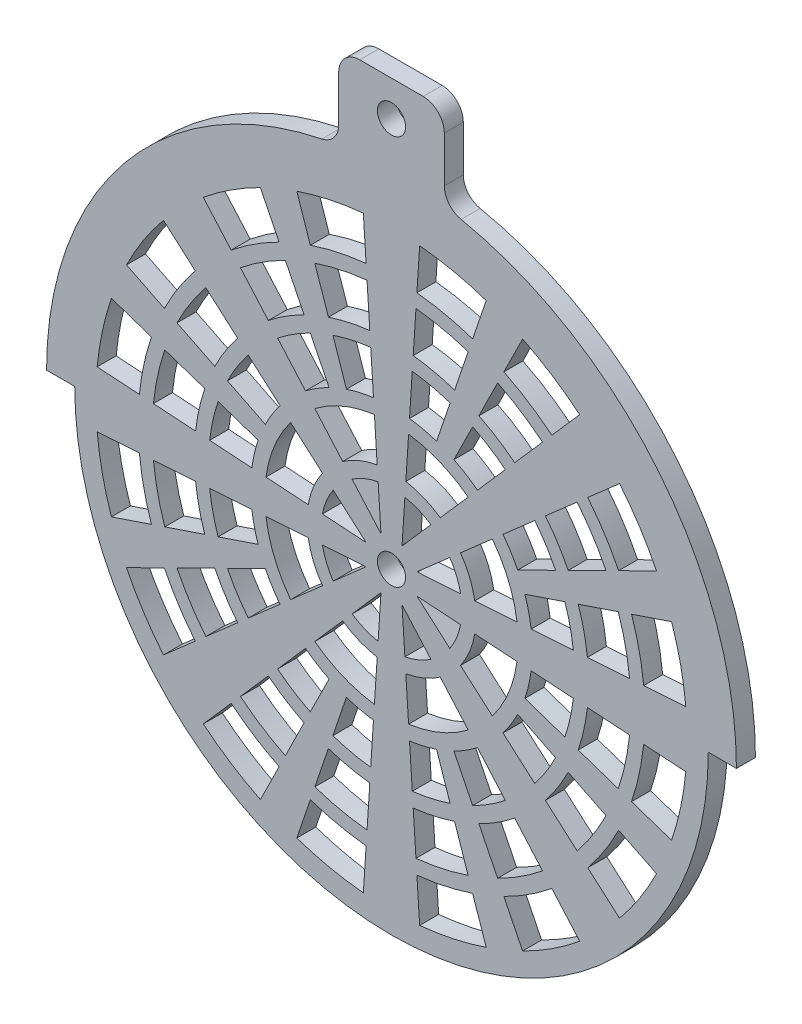
SolidWorks part; units mm, degrees
ref_plane "前基準面" through (0, 0, 0) normal (0, 0, 1) x (1, 0, 0)
ref_plane "上基準面" through (0, 0, 0) normal (0, 1, 0) x (1, 0, 0)
ref_plane "右基準面" through (0, 0, 0) normal (1, 0, 0) x (0, 0, -1)
sketch "草圖1" plane through (0, 0, 0) normal (0, 0, 1) x (1, 0, 0)
  line L0 (-49, 0) -> (-45, 0)
  line L1 (45, 0) -> (49, 0)
  arc A0 (49, 0) -> (-49, 0) centre (0, 0) ccw
  arc A1 (-45, 0) -> (45, 0) centre (0, 0) ccw
  circle A2 centre (0, 0) radius 42
  dimension "D1" = 98
  dimension "D2" = 90
  dimension "D3" = 3
extrude "填料-伸長1" add sketch "草圖1" along normal blind 2.7
sketch "草圖2" plane through (0, 0, 2.7) normal (0, 0, 1) x (1, 0, 0)
  line L0 (0, 4) -> (0, 42) construction
  line L1 (-1.5, 3.7081) -> (-1.9009, 9.8177)
  line L2 (1.5, 3.7081) -> (1.9009, 9.8177)
  line L3 (3.6827, 1.5614) -> (8.2863, 5.598)
  line L4 (1.5614, 3.6827) -> (5.598, 8.2863)
  line L5 (3.7081, -1.5) -> (9.8177, -1.9009)
  line L6 (3.7081, 1.5) -> (9.8177, 1.9009)
  line L7 (1.5614, -3.6827) -> (5.598, -8.2863)
  line L8 (3.6827, -1.5614) -> (8.2863, -5.598)
  line L9 (-1.5, -3.7081) -> (-1.9009, -9.8177)
  line L10 (1.5, -3.7081) -> (1.9009, -9.8177)
  line L11 (-3.6827, -1.5614) -> (-8.2863, -5.598)
  line L12 (-1.5614, -3.6827) -> (-5.598, -8.2863)
  line L13 (-3.7081, 1.5) -> (-9.8177, 1.9009)
  line L14 (-3.7081, -1.5) -> (-9.8177, -1.9009)
  line L15 (-1.5614, 3.6827) -> (-5.598, 8.2863)
  line L16 (-3.6827, 1.5614) -> (-8.2863, 5.598)
  line L17 (1.5307, 3.6955) -> (16.0727, 38.8029) construction
  line L22 (18.947, 6.4041) -> (24.6311, 8.3253)
  line L23 (17.9266, 8.8678) -> (23.3045, 11.5282)
  line L24 (8.8691, 17.9259) -> (15.0775, 30.474)
  line L25 (6.4055, 18.9465) -> (8.3272, 24.6304)
  line L26 (17.9259, -8.8691) -> (23.3037, -11.5299)
  line L27 (18.9465, -6.4055) -> (24.6304, -8.3272)
  line L28 (6.4041, -18.947) -> (8.3253, -24.6311)
  line L29 (8.8678, -17.9266) -> (11.5282, -23.3045)
  line L30 (-8.8691, -17.9259) -> (-11.5299, -23.3037)
  line L31 (-6.4055, -18.9465) -> (-8.3272, -24.6304)
  line L32 (-18.947, -6.4041) -> (-24.6311, -8.3253)
  line L33 (-17.9266, -8.8678) -> (-23.3045, -11.5282)
  line L34 (-17.9259, 8.8691) -> (-23.3037, 11.5299)
  line L35 (-18.9465, 6.4055) -> (-24.6304, 8.3272)
  line L36 (-6.4041, 18.947) -> (-8.3253, 24.6311)
  line L37 (-8.8678, 17.9266) -> (-11.5282, 23.3045)
  line L38 (-3.6069, 35.8188) -> (-4, 41.8091)
  line L39 (3.6069, 35.8188) -> (4, 41.8091)
  line L40 (11.5299, 34.1037) -> (13.4516, 39.7876)
  line L41 (15.9645, 32.2666) -> (18.6252, 37.6444)
  line L42 (22.7773, 27.8782) -> (26.7351, 32.3919)
  line L43 (27.8782, 22.7773) -> (32.3919, 26.7351)
  line L44 (32.2678, 15.9621) -> (37.6458, 18.6224)
  line L45 (34.1045, 11.5274) -> (39.7886, 13.4486)
  line L46 (-11.5274, 34.1045) -> (-13.4486, 39.7886)
  line L47 (-15.9621, 32.2678) -> (-18.6224, 37.6458)
  line L48 (-22.7773, 27.8782) -> (-26.7351, 32.3919)
  line L49 (-27.8782, 22.7773) -> (-32.3919, 26.7351)
  line L50 (-32.2666, 15.9645) -> (-37.6444, 18.6252)
  line L51 (-34.1037, 11.5299) -> (-39.7876, 13.4516)
  line L52 (-35.8188, 3.6069) -> (-41.8091, 4)
  line L53 (-35.8188, -3.6069) -> (-41.8091, -4)
  line L54 (-34.1045, -11.5274) -> (-39.7886, -13.4486)
  line L55 (-32.2678, -15.9621) -> (-37.6458, -18.6224)
  line L56 (-27.8782, -22.7773) -> (-32.3919, -26.7351)
  line L57 (-22.7773, -27.8782) -> (-26.7351, -32.3919)
  line L58 (-15.9645, -32.2666) -> (-18.6252, -37.6444)
  line L59 (-11.5299, -34.1037) -> (-13.4516, -39.7876)
  line L60 (-3.6069, -35.8188) -> (-4, -41.8091)
  line L61 (3.6069, -35.8188) -> (4, -41.8091)
  line L62 (11.5274, -34.1045) -> (13.4486, -39.7886)
  line L63 (15.9621, -32.2678) -> (18.6224, -37.6458)
  line L64 (22.7773, -27.8782) -> (26.7351, -32.3919)
  line L65 (27.8782, -22.7773) -> (32.3919, -26.7351)
  line L66 (32.2666, -15.9645) -> (37.6444, -18.6252)
  line L67 (35.8188, -3.6069) -> (41.8091, -4)
  line L68 (34.1037, -11.5299) -> (39.7876, -13.4516)
  line L69 (35.8188, 3.6069) -> (41.8091, 4)
  line L70 (17.4988, 21.8585) -> (21.4578, 26.3735)
  line L71 (21.8585, 17.4988) -> (26.3735, 21.4578)
  line L72 (25.0972, 12.4149) -> (30.4752, 15.0753)
  line L73 (26.5258, 8.9657) -> (32.2098, 10.887)
  line L74 (27.8298, 3.0827) -> (33.8219, 3.4759)
  line L75 (27.8298, -3.0827) -> (33.8219, -3.4759)
  line L76 (26.5251, -8.9677) -> (32.209, -10.8894)
  line L77 (25.0963, -12.4168) -> (30.474, -15.0775)
  line L78 (21.8585, -17.4988) -> (26.3735, -21.4578)
  line L79 (17.4988, -21.8585) -> (21.4578, -26.3735)
  line L80 (12.4149, -25.0972) -> (15.0753, -30.4752)
  line L81 (8.9657, -26.5258) -> (10.887, -32.2098)
  line L82 (3.0827, -27.8298) -> (3.4759, -33.8219)
  line L83 (-3.0827, -27.8298) -> (-3.4759, -33.8219)
  line L84 (-8.9677, -26.5251) -> (-10.8894, -32.209)
  line L85 (-12.4168, -25.0963) -> (-15.0775, -30.474)
  line L86 (-17.4988, -21.8585) -> (-21.4578, -26.3735)
  line L87 (-21.8585, -17.4988) -> (-26.3735, -21.4578)
  line L88 (-25.0972, -12.4149) -> (-30.4752, -15.0753)
  line L89 (-26.5258, -8.9657) -> (-32.2098, -10.887)
  line L90 (-27.8298, -3.0827) -> (-33.8219, -3.4759)
  line L91 (-27.8298, 3.0827) -> (-33.8219, 3.4759)
  line L92 (-26.5251, 8.9677) -> (-32.209, 10.8894)
  line L93 (-25.0963, 12.4168) -> (-30.474, 15.0775)
  line L94 (-21.8585, 17.4988) -> (-26.3735, 21.4578)
  line L95 (-17.4988, 21.8585) -> (-21.4578, 26.3735)
  line L96 (-12.4149, 25.0972) -> (-15.0753, 30.4752)
  line L97 (-8.9657, 26.5258) -> (-10.887, 32.2098)
  line L98 (-3.0827, 27.8298) -> (-3.4759, 33.8219)
  line L99 (3.0827, 27.8298) -> (3.4759, 33.8219)
  line L100 (8.9677, 26.5251) -> (10.8894, 32.209)
  line L101 (-12.217, 15.8349) -> (-16.1788, 20.3531)
  line L102 (-15.8349, 12.217) -> (-20.3531, 16.1788)
  line L103 (-19.8357, 2.5582) -> (-25.8319, 2.9517)
  line L104 (-19.8357, -2.5582) -> (-25.8319, -2.9517)
  line L105 (-15.8349, -12.217) -> (-20.3531, -16.1788)
  line L106 (-12.217, -15.8349) -> (-16.1788, -20.3531)
  line L107 (-2.5582, -19.8357) -> (-2.9517, -25.8319)
  line L108 (2.5582, -19.8357) -> (2.9517, -25.8319)
  line L109 (12.217, -15.8349) -> (16.1788, -20.3531)
  line L110 (15.8349, -12.217) -> (20.3531, -16.1788)
  line L111 (19.8357, -2.5582) -> (25.8319, -2.9517)
  line L112 (19.8357, 2.5582) -> (25.8319, 2.9517)
  line L113 (15.8349, 12.217) -> (20.3531, 16.1788)
  line L114 (12.217, 15.8349) -> (16.1788, 20.3531)
  line L115 (-2.5582, 19.8357) -> (-2.9517, 25.8319)
  line L116 (2.5582, 19.8357) -> (2.9517, 25.8319)
  line L117 (6.9253, -9.8) -> (10.8956, -14.3278)
  line L118 (9.8, -6.9253) -> (14.3278, -10.8956)
  line L119 (11.8266, -2.0327) -> (17.8356, -2.427)
  line L120 (11.8266, 2.0327) -> (17.8356, 2.427)
  line L121 (9.8, 6.9253) -> (14.3278, 10.8956)
  line L122 (6.9253, 9.8) -> (10.8956, 14.3278)
  line L123 (2.0327, 11.8266) -> (2.427, 17.8356)
  line L124 (-2.0327, 11.8266) -> (-2.427, 17.8356)
  line L125 (-6.9253, 9.8) -> (-10.8956, 14.3278)
  line L126 (-9.8, 6.9253) -> (-14.3278, 10.8956)
  line L127 (-11.8266, 2.0327) -> (-17.8356, 2.427)
  line L128 (-11.8266, -2.0327) -> (-17.8356, -2.427)
  line L129 (-9.8, -6.9253) -> (-14.3278, -10.8956)
  line L130 (-6.9253, -9.8) -> (-10.8956, -14.3278)
  line L131 (-2.0327, -11.8266) -> (-2.427, -17.8356)
  line L132 (2.0327, -11.8266) -> (2.427, -17.8356)
  arc A0 (8.9677, 26.5251) -> (3.0827, 27.8298) centre (0, 0) ccw
  arc A1 (21.4578, 26.3735) -> (15.0775, 30.474) centre (0, 0) ccw
  circle A2 centre (0, 0) radius 36
  arc A3 (22.7773, 27.8782) -> (15.9645, 32.2666) centre (0, 0) ccw
  arc A6 (22.7773, 27.8782) -> (15.9645, 32.2666) centre (0, 0) ccw
  arc A7 (21.4578, 26.3735) -> (15.0775, 30.474) centre (0, 0) ccw
  arc A8 (-11.5282, 23.3045) -> (-16.1788, 20.3531) centre (0, 0) ccw
  arc A9 (-8.8678, 17.9266) -> (-12.217, 15.8349) centre (0, 0) ccw
  arc A10 (-2.427, 17.8356) -> (-10.8956, 14.3278) centre (0, 0) ccw
  arc A11 (-6.9253, -9.8) -> (-2.0327, -11.8266) centre (0, 0) ccw
  arc A12 (-5.598, -8.2863) -> (-1.9009, -9.8177) centre (0, 0) ccw
  arc A14 (-3.6827, 1.5614) -> (-3.7081, 1.5) centre (0, 0) ccw
  circle A15 centre (0, 0) radius 42 construction
  arc A16 (4, 41.8091) -> (-4, 41.8091) centre (0, 0) ccw
  arc A17 (18.6252, 37.6444) -> (13.4516, 39.7876) centre (0, 0) ccw
  arc A18 (32.3919, 26.7351) -> (26.7351, 32.3919) centre (0, 0) ccw
  arc A19 (39.7886, 13.4486) -> (37.6458, 18.6224) centre (0, 0) ccw
  arc A20 (41.8091, -4) -> (41.8091, 4) centre (0, 0) ccw
  arc A21 (37.6444, -18.6252) -> (39.7876, -13.4516) centre (0, 0) ccw
  arc A22 (26.7351, -32.3919) -> (32.3919, -26.7351) centre (0, 0) ccw
  arc A23 (13.4486, -39.7886) -> (18.6224, -37.6458) centre (0, 0) ccw
  arc A24 (-4, -41.8091) -> (4, -41.8091) centre (0, 0) ccw
  arc A25 (-18.6252, -37.6444) -> (-13.4516, -39.7876) centre (0, 0) ccw
  arc A26 (-32.3919, -26.7351) -> (-26.7351, -32.3919) centre (0, 0) ccw
  arc A27 (-39.7886, -13.4486) -> (-37.6458, -18.6224) centre (0, 0) ccw
  arc A28 (-41.8091, 4) -> (-41.8091, -4) centre (0, 0) ccw
  arc A29 (-37.6444, 18.6252) -> (-39.7876, 13.4516) centre (0, 0) ccw
  arc A30 (-26.7351, 32.3919) -> (-32.3919, 26.7351) centre (0, 0) ccw
  arc A31 (-13.4486, 39.7886) -> (-18.6224, 37.6458) centre (0, 0) ccw
  circle A32 centre (0, 0) radius 36 construction
  circle A33 centre (0, 0) radius 34 construction
  arc A34 (32.2678, 15.9621) -> (27.8782, 22.7773) centre (0, 0) ccw
  arc A35 (32.2678, 15.9621) -> (27.8782, 22.7773) centre (0, 0) ccw
  arc A36 (30.4752, 15.0753) -> (26.3735, 21.4578) centre (0, 0) ccw
  arc A37 (30.4752, 15.0753) -> (26.3735, 21.4578) centre (0, 0) ccw
  arc A38 (35.8188, 3.6069) -> (34.1045, 11.5274) centre (0, 0) ccw
  arc A39 (35.8188, 3.6069) -> (34.1045, 11.5274) centre (0, 0) ccw
  arc A40 (33.8219, 3.4759) -> (32.2098, 10.887) centre (0, 0) ccw
  arc A41 (33.8219, 3.4759) -> (32.2098, 10.887) centre (0, 0) ccw
  arc A42 (34.1037, -11.5299) -> (35.8188, -3.6069) centre (0, 0) ccw
  arc A43 (34.1037, -11.5299) -> (35.8188, -3.6069) centre (0, 0) ccw
  arc A44 (32.209, -10.8894) -> (33.8219, -3.4759) centre (0, 0) ccw
  arc A45 (32.209, -10.8894) -> (33.8219, -3.4759) centre (0, 0) ccw
  arc A46 (27.8782, -22.7773) -> (32.2666, -15.9645) centre (0, 0) ccw
  arc A47 (27.8782, -22.7773) -> (32.2666, -15.9645) centre (0, 0) ccw
  arc A48 (26.3735, -21.4578) -> (30.474, -15.0775) centre (0, 0) ccw
  arc A49 (26.3735, -21.4578) -> (30.474, -15.0775) centre (0, 0) ccw
  arc A50 (15.9621, -32.2678) -> (22.7773, -27.8782) centre (0, 0) ccw
  arc A51 (15.9621, -32.2678) -> (22.7773, -27.8782) centre (0, 0) ccw
  arc A52 (15.0753, -30.4752) -> (21.4578, -26.3735) centre (0, 0) ccw
  arc A53 (15.0753, -30.4752) -> (21.4578, -26.3735) centre (0, 0) ccw
  arc A54 (3.6069, -35.8188) -> (11.5274, -34.1045) centre (0, 0) ccw
  arc A55 (3.6069, -35.8188) -> (11.5274, -34.1045) centre (0, 0) ccw
  arc A56 (3.4759, -33.8219) -> (10.887, -32.2098) centre (0, 0) ccw
  arc A57 (3.4759, -33.8219) -> (10.887, -32.2098) centre (0, 0) ccw
  arc A58 (-11.5299, -34.1037) -> (-3.6069, -35.8188) centre (0, 0) ccw
  arc A59 (-11.5299, -34.1037) -> (-3.6069, -35.8188) centre (0, 0) ccw
  arc A60 (-10.8894, -32.209) -> (-3.4759, -33.8219) centre (0, 0) ccw
  arc A61 (-10.8894, -32.209) -> (-3.4759, -33.8219) centre (0, 0) ccw
  arc A62 (-22.7773, -27.8782) -> (-15.9645, -32.2666) centre (0, 0) ccw
  arc A63 (-22.7773, -27.8782) -> (-15.9645, -32.2666) centre (0, 0) ccw
  arc A64 (-21.4578, -26.3735) -> (-15.0775, -30.474) centre (0, 0) ccw
  arc A65 (-21.4578, -26.3735) -> (-15.0775, -30.474) centre (0, 0) ccw
  arc A66 (-32.2678, -15.9621) -> (-27.8782, -22.7773) centre (0, 0) ccw
  arc A67 (-32.2678, -15.9621) -> (-27.8782, -22.7773) centre (0, 0) ccw
  arc A68 (-30.4752, -15.0753) -> (-26.3735, -21.4578) centre (0, 0) ccw
  arc A69 (-30.4752, -15.0753) -> (-26.3735, -21.4578) centre (0, 0) ccw
  arc A70 (-35.8188, -3.6069) -> (-34.1045, -11.5274) centre (0, 0) ccw
  arc A71 (-35.8188, -3.6069) -> (-34.1045, -11.5274) centre (0, 0) ccw
  arc A72 (-33.8219, -3.4759) -> (-32.2098, -10.887) centre (0, 0) ccw
  arc A73 (-33.8219, -3.4759) -> (-32.2098, -10.887) centre (0, 0) ccw
  arc A74 (-34.1037, 11.5299) -> (-35.8188, 3.6069) centre (0, 0) ccw
  arc A75 (-34.1037, 11.5299) -> (-35.8188, 3.6069) centre (0, 0) ccw
  arc A76 (-32.209, 10.8894) -> (-33.8219, 3.4759) centre (0, 0) ccw
  arc A77 (-32.209, 10.8894) -> (-33.8219, 3.4759) centre (0, 0) ccw
  arc A78 (-27.8782, 22.7773) -> (-32.2666, 15.9645) centre (0, 0) ccw
  arc A79 (-27.8782, 22.7773) -> (-32.2666, 15.9645) centre (0, 0) ccw
  arc A80 (-26.3735, 21.4578) -> (-30.474, 15.0775) centre (0, 0) ccw
  arc A81 (-26.3735, 21.4578) -> (-30.474, 15.0775) centre (0, 0) ccw
  arc A82 (-15.9621, 32.2678) -> (-22.7773, 27.8782) centre (0, 0) ccw
  arc A83 (-15.9621, 32.2678) -> (-22.7773, 27.8782) centre (0, 0) ccw
  arc A84 (-15.0753, 30.4752) -> (-21.4578, 26.3735) centre (0, 0) ccw
  arc A85 (-15.0753, 30.4752) -> (-21.4578, 26.3735) centre (0, 0) ccw
  arc A86 (11.5299, 34.1037) -> (3.6069, 35.8188) centre (0, 0) ccw
  arc A87 (11.5299, 34.1037) -> (3.6069, 35.8188) centre (0, 0) ccw
  arc A88 (10.8894, 32.209) -> (3.4759, 33.8219) centre (0, 0) ccw
  arc A89 (10.8894, 32.209) -> (3.4759, 33.8219) centre (0, 0) ccw
  circle A90 centre (0, 0) radius 28 construction
  arc A91 (-3.0827, 27.8298) -> (-8.9657, 26.5258) centre (0, 0) ccw
  arc A92 (-3.6069, 35.8188) -> (-11.5274, 34.1045) centre (0, 0) ccw
  arc A93 (-3.6069, 35.8188) -> (-11.5274, 34.1045) centre (0, 0) ccw
  arc A94 (-3.4759, 33.8219) -> (-10.887, 32.2098) centre (0, 0) ccw
  arc A95 (-3.4759, 33.8219) -> (-10.887, 32.2098) centre (0, 0) ccw
  arc A96 (-12.4149, 25.0972) -> (-17.4988, 21.8585) centre (0, 0) ccw
  circle A97 centre (0, 0) radius 26 construction
  arc A98 (-21.8585, 17.4988) -> (-25.0963, 12.4168) centre (0, 0) ccw
  arc A99 (-20.3531, 16.1788) -> (-23.3037, 11.5299) centre (0, 0) ccw
  arc A100 (-26.5251, 8.9677) -> (-27.8298, 3.0827) centre (0, 0) ccw
  arc A101 (-24.6304, 8.3272) -> (-25.8319, 2.9517) centre (0, 0) ccw
  arc A102 (-27.8298, -3.0827) -> (-26.5258, -8.9657) centre (0, 0) ccw
  arc A103 (-25.8319, -2.9517) -> (-24.6311, -8.3253) centre (0, 0) ccw
  arc A104 (-25.0972, -12.4149) -> (-21.8585, -17.4988) centre (0, 0) ccw
  arc A105 (-23.3045, -11.5282) -> (-20.3531, -16.1788) centre (0, 0) ccw
  arc A106 (-17.4988, -21.8585) -> (-12.4168, -25.0963) centre (0, 0) ccw
  arc A107 (-16.1788, -20.3531) -> (-11.5299, -23.3037) centre (0, 0) ccw
  arc A108 (-8.9677, -26.5251) -> (-3.0827, -27.8298) centre (0, 0) ccw
  arc A109 (-8.3272, -24.6304) -> (-2.9517, -25.8319) centre (0, 0) ccw
  arc A110 (3.0827, -27.8298) -> (8.9657, -26.5258) centre (0, 0) ccw
  arc A111 (2.9517, -25.8319) -> (8.3253, -24.6311) centre (0, 0) ccw
  arc A112 (12.4149, -25.0972) -> (17.4988, -21.8585) centre (0, 0) ccw
  arc A113 (11.5282, -23.3045) -> (16.1788, -20.3531) centre (0, 0) ccw
  arc A114 (21.8585, -17.4988) -> (25.0963, -12.4168) centre (0, 0) ccw
  arc A115 (20.3531, -16.1788) -> (23.3037, -11.5299) centre (0, 0) ccw
  arc A116 (26.5251, -8.9677) -> (27.8298, -3.0827) centre (0, 0) ccw
  arc A117 (24.6304, -8.3272) -> (25.8319, -2.9517) centre (0, 0) ccw
  arc A118 (27.8298, 3.0827) -> (26.5258, 8.9657) centre (0, 0) ccw
  arc A119 (25.8319, 2.9517) -> (24.6311, 8.3253) centre (0, 0) ccw
  arc A120 (25.0972, 12.4149) -> (21.8585, 17.4988) centre (0, 0) ccw
  arc A121 (23.3045, 11.5282) -> (20.3531, 16.1788) centre (0, 0) ccw
  arc A122 (17.4988, 21.8585) -> (12.4168, 25.0963) centre (0, 0) ccw
  arc A123 (16.1788, 20.3531) -> (11.5299, 23.3037) centre (0, 0) ccw
  arc A124 (8.3272, 24.6304) -> (2.9517, 25.8319) centre (0, 0) ccw
  arc A125 (-2.9517, 25.8319) -> (-8.3253, 24.6311) centre (0, 0) ccw
  circle A126 centre (0, 0) radius 20 construction
  arc A127 (-15.8349, 12.217) -> (-17.9259, 8.8691) centre (0, 0) ccw
  arc A128 (-18.9465, 6.4055) -> (-19.8357, 2.5582) centre (0, 0) ccw
  arc A129 (-19.8357, -2.5582) -> (-18.947, -6.4041) centre (0, 0) ccw
  arc A130 (-2.5582, 19.8357) -> (-6.4041, 18.947) centre (0, 0) ccw
  circle A131 centre (0, 0) radius 18 construction
  arc A132 (6.4055, 18.9465) -> (2.5582, 19.8357) centre (0, 0) ccw
  arc A133 (12.217, 15.8349) -> (8.8691, 17.9259) centre (0, 0) ccw
  arc A134 (10.8956, 14.3278) -> (2.427, 17.8356) centre (0, 0) ccw
  arc A135 (17.9266, 8.8678) -> (15.8349, 12.217) centre (0, 0) ccw
  arc A136 (19.8357, 2.5582) -> (18.947, 6.4041) centre (0, 0) ccw
  arc A137 (18.9465, -6.4055) -> (19.8357, -2.5582) centre (0, 0) ccw
  arc A138 (15.8349, -12.217) -> (17.9259, -8.8691) centre (0, 0) ccw
  arc A139 (8.8678, -17.9266) -> (12.217, -15.8349) centre (0, 0) ccw
  arc A140 (2.5582, -19.8357) -> (6.4041, -18.947) centre (0, 0) ccw
  arc A141 (-6.4055, -18.9465) -> (-2.5582, -19.8357) centre (0, 0) ccw
  arc A142 (-17.9266, -8.8678) -> (-15.8349, -12.217) centre (0, 0) ccw
  arc A143 (-12.217, -15.8349) -> (-8.8691, -17.9259) centre (0, 0) ccw
  arc A144 (-10.8956, -14.3278) -> (-2.427, -17.8356) centre (0, 0) ccw
  arc A145 (-17.8356, -2.427) -> (-14.3278, -10.8956) centre (0, 0) ccw
  arc A146 (-14.3278, 10.8956) -> (-17.8356, 2.427) centre (0, 0) ccw
  arc A147 (17.8356, 2.427) -> (14.3278, 10.8956) centre (0, 0) ccw
  arc A148 (14.3278, -10.8956) -> (17.8356, -2.427) centre (0, 0) ccw
  arc A149 (2.427, -17.8356) -> (10.8956, -14.3278) centre (0, 0) ccw
  circle A150 centre (0, 0) radius 12 construction
  circle A151 centre (0, 0) radius 10 construction
  arc A152 (-11.8266, -2.0327) -> (-9.8, -6.9253) centre (0, 0) ccw
  arc A153 (-9.8177, -1.9009) -> (-8.2863, -5.598) centre (0, 0) ccw
  arc A154 (-9.8, 6.9253) -> (-11.8266, 2.0327) centre (0, 0) ccw
  arc A155 (-8.2863, 5.598) -> (-9.8177, 1.9009) centre (0, 0) ccw
  arc A156 (-2.0327, 11.8266) -> (-6.9253, 9.8) centre (0, 0) ccw
  arc A157 (-1.9009, 9.8177) -> (-5.598, 8.2863) centre (0, 0) ccw
  arc A158 (6.9253, 9.8) -> (2.0327, 11.8266) centre (0, 0) ccw
  arc A159 (5.598, 8.2863) -> (1.9009, 9.8177) centre (0, 0) ccw
  arc A160 (11.8266, 2.0327) -> (9.8, 6.9253) centre (0, 0) ccw
  arc A161 (9.8177, 1.9009) -> (8.2863, 5.598) centre (0, 0) ccw
  arc A162 (9.8, -6.9253) -> (11.8266, -2.0327) centre (0, 0) ccw
  arc A163 (8.2863, -5.598) -> (9.8177, -1.9009) centre (0, 0) ccw
  arc A164 (2.0327, -11.8266) -> (6.9253, -9.8) centre (0, 0) ccw
  arc A165 (1.9009, -9.8177) -> (5.598, -8.2863) centre (0, 0) ccw
  circle A166 centre (0, 0) radius 2
  circle A167 centre (0, 0) radius 4 construction
  arc A168 (-1.5, 3.7081) -> (-1.5614, 3.6827) centre (0, 0) ccw
  arc A169 (1.5614, 3.6827) -> (1.5, 3.7081) centre (0, 0) ccw
  arc A170 (3.7081, 1.5) -> (3.6827, 1.5614) centre (0, 0) ccw
  arc A171 (3.6827, -1.5614) -> (3.7081, -1.5) centre (0, 0) ccw
  arc A172 (1.5, -3.7081) -> (1.5614, -3.6827) centre (0, 0) ccw
  arc A173 (-1.5614, -3.6827) -> (-1.5, -3.7081) centre (0, 0) ccw
  arc A174 (-3.7081, -1.5) -> (-3.6827, -1.5614) centre (0, 0) ccw
  point P25 (16.1788, 20.3531)
  point P33 (13.9841, 33.7606)
  point P65 (0, 0)
  point P66 (2.9517, 25.8319)
  point P67 (16.6604, 40.2218)
  point P72 (9.5734, 12.8199)
  point P73 (2.2957, 15.8345)
  point P74 (14.2067, 39.5243)
  point P105 (0, 0)
  circle M18 centre (0, 0) radius 42
  dimension "D11" = 8
  dimension "D12" = 4
  dimension "D13" = 3
  dimension "D14" = 1.5
  dimension "D16" = 22.5
  dimension "D17" = 5.6
  dimension "D18" = 2.8
  dimension "D1" = 6
  dimension "D2" = 2
  dimension "D3" = 6
  dimension "D4" = 2
  dimension "D5" = 6
  dimension "D6" = 2
  dimension "D7" = 6
  dimension "D8" = 2
  dimension "D9" = 8
  dimension "D10" = 6
  dimension "D19" = 2
  dimension "D15" = 8
extrude "填料-伸長2" add sketch "草圖2" against normal blind 2.7 contours L38 A92 L46 L47 A82 L48 L49 A78 L50 L51 A74 L52 L53 A70 L54 L55 A66 L56 L57 A62 L58 L59 A58 L60 L61 A54 L62 L63 A50 L64 L65 A46 L66 L68 A42 L67 L69 A38 L45 M18
sketch "草圖3" plane through (0, 0, 2.7) normal (0, 0, 1) x (1, 0, 0)
  line L2 (-7.5, 48.4226) -> (-7.5, 57.4226)
  line L3 (-4.5, 60.4226) -> (4.5, 60.4226)
  line L4 (7.5, 48.4226) -> (7.5, 57.4226)
  line L5 (-7.5, 48.4226) -> (7.5, 48.4226)
  arc A0 (49, 0) -> (-49, 0) centre (0, 0) ccw construction
  arc A1 (4.5, 60.4226) -> (7.5, 57.4226) centre (4.5, 57.4226) cw
  arc A2 (-7.5, 57.4226) -> (-4.5, 60.4226) centre (-4.5, 57.4226) cw
  circle A3 centre (0, 55.4226) radius 2
  point P10 (0, 49)
  point P14 (0, 60.4226)
  dimension "D3" = 3
  dimension "D4" = 4
  dimension "D1" = 12
  dimension "D2" = 15
  dimension "D5" = 5
extrude "填料-伸長3" add sketch "草圖3" against normal blind 2.7
fillet "圓角1" radius 3 2 edges at (-7.5, 48.4226, 1.35) (7.5, 48.4226, 1.35)
